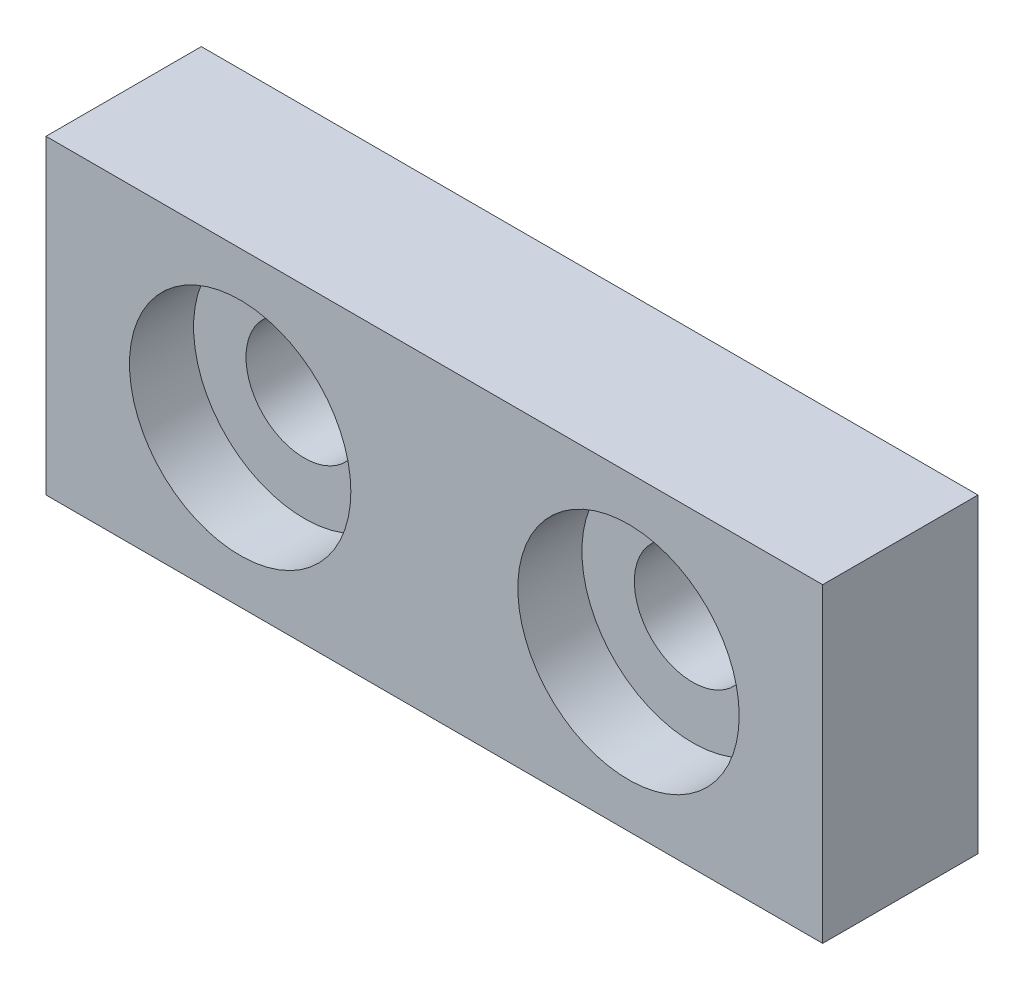
SolidWorks part; units mm, degrees
ref_plane "Alzado" through (0, 0, 0) normal (0, 0, 1) x (1, 0, 0)
ref_plane "Planta" through (0, 0, 0) normal (0, 1, 0) x (1, 0, 0)
ref_plane "Vista lateral" through (0, 0, 0) normal (1, 0, 0) x (0, 0, -1)
sketch "Croquis1" plane through (0, 0, 0) normal (0, 0, 1) x (1, 0, 0)
  line L0 (-55, 75) -> (-3, 75) construction
  line L1 (-71, 75) -> (-55, 75) construction
  line L2 (-3, 83) -> (-3, 62) construction
  line L3 (-44.5, 4) -> (-44.5, 65) construction
  line L4 (-82, 4) -> (-7, 4)
  line L5 (-82, 4) -> (-82, 65)
  line L6 (-82, 65) -> (-7, 65)
  line L7 (-7, 4) -> (-7, 65)
  line L8 (-44.5, 65) -> (-34.5, 73) construction
  line L9 (-44.5, 65) -> (-54.5, 65)
  line L10 (-44.5, 65) -> (-44.5, 73) construction
  line L11 (-44.5, 73) -> (-54.5, 73)
  line L12 (-54.5, 65) -> (-54.5, 73)
  line L13 (-44.5, 65) -> (-34.5, 65)
  line L14 (-44.5, 65) -> (-44.5, 73)
  line L15 (-44.5, 73) -> (-34.5, 73)
  line L16 (-34.5, 65) -> (-34.5, 73)
  line L17 (-44.5, 73) -> (-34.5, 65) construction
  line L18 (-44.5, 73) -> (-54.5, 65) construction
  line L19 (-54.5, 73) -> (-44.5, 65) construction
  circle A0 centre (-49.5, 69) radius 1.5
  circle A1 centre (-39.5, 69) radius 1.5
  dimension "D6" = 3
  dimension "D7" = 3
  dimension "D1" = 61
  dimension "D2" = 75
  dimension "D3" = 8
  dimension "D4" = 10
  dimension "D5" = 10
extrude "Saliente-Extruir1" add sketch "Croquis1" along normal blind 4 contours L6 L16 L15 L14 A1 | L6 L14 L11 L12 A0
sketch "Croquis2" plane through (0, 0, 4) normal (0, 0, 1) x (1, 0, 0)
  circle A0 centre (-49.5, 69) radius 2.85
  circle A1 centre (-39.5, 69) radius 2.85
  dimension "D1" = 5.7
  dimension "D2" = 5.7
extrude "Cortar-Extruir1" cut sketch "Croquis2" against normal blind 1.65 contours A1 | A0
